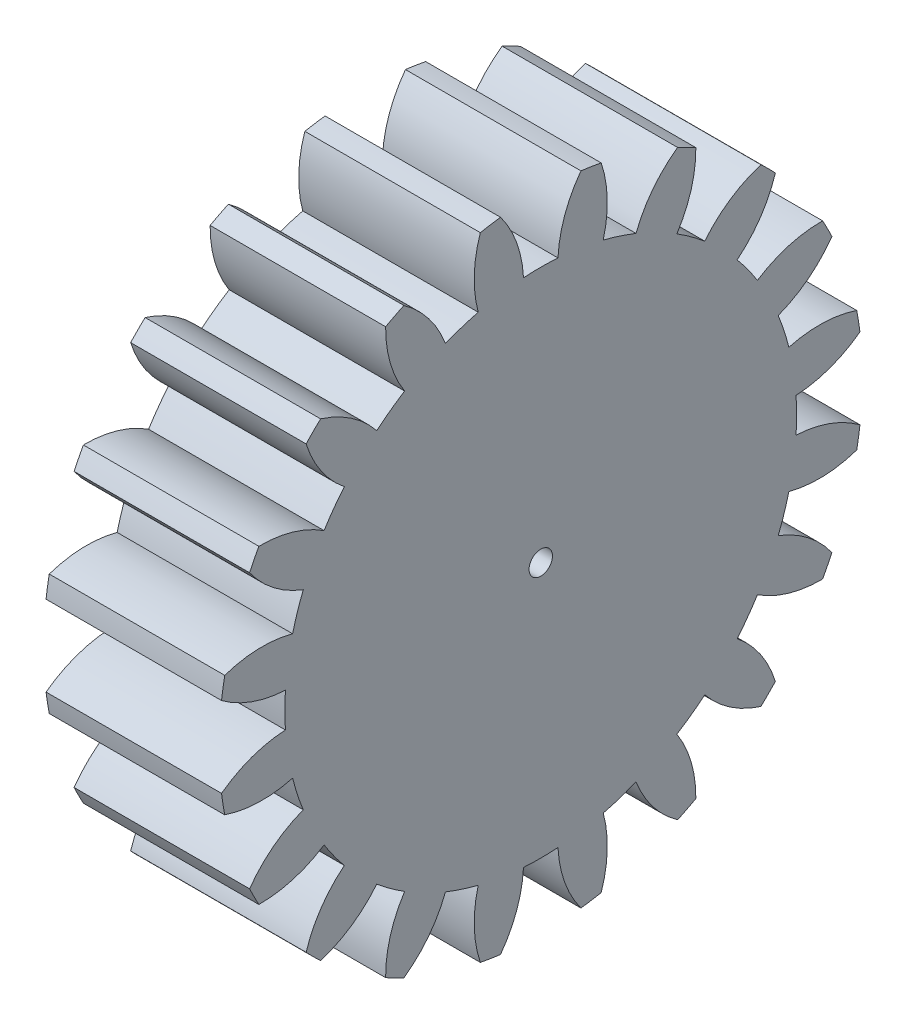
SolidWorks part; units mm, degrees
ref_plane "Plane1" through (0, 0, 0) normal (0, 0, 1) x (1, 0, 0)
ref_plane "Plane2" through (0, 0, 0) normal (0, 1, 0) x (1, 0, 0)
ref_plane "Plane3" through (0, 0, 0) normal (1, 0, 0) x (0, 0, -1)
other "Configuration Table"
sketch "HoldingSke" plane through (0, 0, 0) normal (0, 1, 0) x (1, 0, 0)
  line L0 (0, 0) -> (0.9397, -0.342)
  line L1 (-15, 0) -> (100, 0) construction
  line L2 (0, 0) -> (-2.1039, 2.3779)
  line L3 (0, 0) -> (-11.863, 4.5341)
  line L4 (0, 0) -> (8.1152, 2.9537)
  line L5 (0, 0) -> (-46.8476, -17.4728)
  line L6 (0, 0) -> (-4.9738, -3.3558)
  line L7 (-2.1039, 2.3779) -> (8.6586, 51.2059)
  line L8 (-76.2, 54.61) -> (-76.1, 54.61)
  line L9 (-67.7845, 28.3722) -> (-49.3413, 33.142)
  line L10 (-76.2, 71.12) -> (104.1128, 71.12)
  line L11 (0, 0) -> (-6, 0)
  line L12 (-76.2, 101.6) -> (-76.162, 101.6)
  line L13 (24.9733, 27.94) -> (52.9518, 28.4284)
  line L14 (24.9733, 27.94) -> (24.9743, 27.94)
  line L15 (24.9733, 27.94) -> (100.4006, 29.5858)
  line L16 (-63.627, -1) -> (-12.827, -1)
  circle A0 centre (0, 0) radius 0.4
  circle A1 centre (0, 0) radius 8.749
  circle A2 centre (0, 0) radius 37.5
  circle A3 centre (0, 0) radius 0.4
  dimension "MHD" = 17.498
  dimension "Hub_dia" = 75
  dimension "Bore" = 0.8
  dimension "MBD" = 0.8
  dimension "Num_teeth" = 20
  dimension "Pitch" = 1
  dimension "Overall_len" = 50
  dimension "Show_teeth" = 20
  dimension "Thickness" = 6
  dimension "OAL" = 50.0001
  dimension "T_dim" = 0.1
  dimension "Ap" = 14.5
  dimension "H" = 19.05
  dimension "Pitch_radius" = 180.3128
  dimension "Width" = 6
  dimension "Backlash" = 0.038
  dimension "Addendum_fac" = 1
  dimension "Dedendum_fac" = 1.25
  dimension "Clearance_fac" = 0.25
  dimension "Dedendum_add" = 0.001
  dimension "Module" = 1
sketch "BasProSke" plane through (0, 0, 0) normal (0, 1, 0) x (1, 0, 0)
  line L0 (-10, 0) -> (60, 0) construction
  line L1 (0, 0) -> (0, 11)
  line L2 (0, 0) -> (6, 0)
  line L3 (6, 0) -> (6, 11)
  line L4 (6, 11) -> (0, 11)
  dimension "Thickness" = 6
  dimension "Diameter" = 22
revolve "Base-Revolve" add sketch "BasProSke" angle 360 about L0
sketch "TooCutSke" plane through (0, 0, 0) normal (1, 0, 0) x (0, 0, -1)
  line L1 (0, 0) -> (0, 107) construction
  line L2 (0, 0) -> (-0.8511, 9.9637) construction
  line L3 (0, 0) -> (-3.1206, 19.7028) construction
  line L4 (-0.8511, 9.9637) -> (-1.5603, 9.8514) construction
  arc A0 (0.5894, 8.7291) -> (-0.5894, 8.7291) centre (0, 0) ccw
  arc A1 (1.3917, 10.9372) -> (-1.3917, 10.9372) centre (0, 0) ccw
  circle A2 centre (0, 0) radius 10 construction
  circle A3 centre (0, 0) radius 9.6815 construction
  arc A4 (-0.5894, 8.7291) -> (-1.3917, 10.9372) centre (-4.5843, 8.5273) ccw
  arc A5 (1.3917, 10.9372) -> (0.5894, 8.7291) centre (4.5843, 8.5273) ccw
  dimension "Root_dia" = 17.498
  dimension "Overcut_dia" = 22.0508
  dimension "Pitch_dia" = 20
  dimension "Base_dia" = 19.363
  dimension "Flank_rad" = 4
  dimension "Half_ang" = 9
  dimension "Half_CT" = 0.7181
extrude "ToothCut" cut sketch "TooCutSke" along normal through all
fillet "Breaks" [suppressed] radius 0.02
fillet "RootFillets" [suppressed] radius 0.251
pattern_circular "TeethCuts" count 20 every 18 about axis through (-10, 0, 0) along (1, 0, 0) of "ToothCut", "RootFillets", "Breaks"
sketch "HubNeaOneSke" plane through (0, 0, 0) normal (-1, 0, 0) x (0, 0, 1)
  circle A0 centre (0, 0) radius 8.749
  dimension "Diameter" = 17.498
extrude "HubNearOne" [suppressed] add sketch "HubNeaOneSke" along normal blind 44.0001
sketch "HubNeaBotSke" plane through (0, 0, 0) normal (-1, 0, 0) x (0, 0, 1)
  circle A0 centre (0, 0) radius 8.749
  dimension "Diameter" = 17.498
extrude "HubNearBoth" [suppressed] add sketch "HubNeaBotSke" along normal blind 22
ref_plane "FarPln" through (6, 0, 0) normal (1, 0, 0) x (0, 0, -1)
sketch "HubFarSke" plane through (6, 0, 0) normal (1, 0, 0) x (0, 0, -1)
  circle A0 centre (0, 0) radius 8.749
  dimension "Diameter" = 17.498
extrude "HubFar" [suppressed] add sketch "HubFarSke" along normal blind 22
sketch "BorSke" plane through (0, 0, 0) normal (1, 0, 0) x (0, 0, -1)
  circle A0 centre (0, 0) radius 0.4
  dimension "Diameter" = 0.8
extrude "Bore" cut sketch "BorSke" along normal mid plane 100.0001
sketch "KeySke" plane through (0, 0, 0) normal (1, 0, 0) x (0, 0, -1)
  line L0 (-0.05, 0) -> (-0.05, 0.5)
  line L1 (-0.05, 0.5) -> (0.05, 0.5)
  line L2 (0.05, 0.5) -> (0.05, 0)
  line L3 (0, 0) -> (0, 34) construction
  line L4 (-0.05, 0) -> (0.05, 0)
  dimension "Offset" = 0.5
  dimension "Width" = 0.1
extrude "Keyway" [suppressed] cut sketch "KeySke" along normal mid plane 100.0001
pattern_circular "Keyway2" [suppressed] count 2 every 90 about axis through (-10, 0, 0) along (1, 0, 0)
equation "' \"Module@HoldingSke\" = 6.35"
equation "' \"Num_teeth@HoldingSke\" = 12"
equation "' \"Ap@HoldingSke\" =  20"
equation "' \"Ap@HoldingSke\" = 20"
equation "' \"Width@HoldingSke\" = 0.5 * 25.4"
equation "' \"Hub_dia@HoldingSke\"= 1 * 25.4"
equation "' \"Hub_dia@HoldingSke\" = 1 * 25.4"
equation "' \"Overall_len@HoldingSke\" = 1.0 * 25.4"
equation "' \"Bore@HoldingSke\" = 0.75 * 25.4"
equation "' \"T_dim@HoldingSke\" = 0.1 * 25.4"
equation "' \"Width@KeySke\" = 0.25 * 25.4"
equation "' \"Show_teeth@HoldingSke\" = 13"
equation "' \"Backlash@HoldingSke\" = 0.009 * 25.4"
equation "' \"Addendum_fac@HoldingSke\" = 1.0"
equation "' \"Dedendum_fac@HoldingSke\" = 1.25"
equation "' \"Dedendum_add@HoldingSke\" = 0.00005 * 25.4"
equation "' \"Clearance_fac@HoldingSke\" = 0.25"
equation "\"Pitch@HoldingSke\" = 1 / \"Module@HoldingSke\""
equation "\"Overcut_dia@TooCutSke\" = (\"Num_teeth@HoldingSke\" + 2 * \"Addendum_fac@HoldingSke\") / \"Pitch@HoldingSke\" + 0.002 * 25.4"
equation "\"Pitch_dia@TooCutSke\" = \"Num_teeth@HoldingSke\" / \"Pitch@HoldingSke\""
equation "\"Base_dia@TooCutSke\" = \"Num_teeth@HoldingSke\" / \"Pitch@HoldingSke\" * cos((\"Ap@HoldingSke\"  * 3.14159265 / 180))"
equation "\"Root_dia@TooCutSke\" = (\"Num_teeth@HoldingSke\" + 2) / \"Pitch@HoldingSke\" - 2 * (\"Addendum_fac@HoldingSke\" + \"Dedendum_fac@HoldingSke\") / \"Pitch@HoldingSke\" - \"Dedendum_add@HoldingSke\" * 2"
equation "\"Half_ang@TooCutSke\" = 180 / \"Num_teeth@HoldingSke\""
equation "\"Half_CT@TooCutSke\" = \"Num_teeth@HoldingSke\" / \"Pitch@HoldingSke\" * sin((3.14159265 / 2 / \"Num_teeth@HoldingSke\")) / 2 - 7 * \"Backlash@HoldingSke\" / 4"
equation "\"Flank_rad@TooCutSke\" = \"Num_teeth@HoldingSke\" / \"Pitch@HoldingSke\" / 5"
equation "\"Radius@RootFillets\" = \"Clearance_fac@HoldingSke\" / \"Pitch@HoldingSke\" + \"Dedendum_add@HoldingSke\""
equation "\"Break_rad@Breaks\" = 0.02 / \"Pitch@HoldingSke\""
equation "\"Thickness@HoldingSke\" = \"Width@HoldingSke\""
equation "\"OAL@HoldingSke\" = \"Thickness@HoldingSke\""
equation "\"MHD@HoldingSke\" = (\"Num_teeth@HoldingSke\" + 2) / \"Pitch@HoldingSke\" - 2 * (\"Addendum_fac@HoldingSke\" + \"Dedendum_fac@HoldingSke\")  / \"Pitch@HoldingSke\" - \"Dedendum_add@HoldingSke\" * 2"
equation "\"MBD@HoldingSke\" = (\"Num_teeth@HoldingSke\" + 2) / \"Pitch@HoldingSke\" - 2 * (\"Addendum_fac@HoldingSke\" + \"Dedendum_fac@HoldingSke\")  / \"Pitch@HoldingSke\" - \"Dedendum_add@HoldingSke\" * 2 - 0.002 * 25.4"
equation "\"MHD@HoldingSke\" = ((sgn( \"MHD@HoldingSke\" - \"Hub_dia@HoldingSke\" )-1)*( \"MHD@HoldingSke\" - \"Hub_dia@HoldingSke\" ))/-2+ \"Hub_dia@HoldingSke\""
equation "\"MBD@HoldingSke\" = ((sgn( \"MBD@HoldingSke\" - \"Bore@HoldingSke\" )-1)*( \"MBD@HoldingSke\" - \"Bore@HoldingSke\" ))/-2+ \"Bore@HoldingSke\""
equation "\"OAL@HoldingSke\" = ((sgn( \"OAL@HoldingSke\" - \"Overall_len@HoldingSke\" )+1)*( \"OAL@HoldingSke\" - \"Overall_len@HoldingSke\" ))/2 + \"Overall_len@HoldingSke\" + 0.000002 * 25.4"
equation "\"Num_teeth@TeethCuts\" = int( \"Show_teeth@HoldingSke\" ) + 1"
equation "\"Num_teeth@TeethCuts\" = ((sgn( \"Num_teeth@TeethCuts\" - \"Num_teeth@HoldingSke\" )-1)*( \"Num_teeth@TeethCuts\" - \"Num_teeth@HoldingSke\" ))/-2+ \"Num_teeth@HoldingSke\""
equation "\"Num_teeth@TeethCuts\" = ((sgn( \"Num_teeth@TeethCuts\" - 2.0)+1)*( \"Num_teeth@TeethCuts\" - 2.0))/2 +2.0"
equation "\"Angle@TeethCuts\" = 360.0 / \"Num_teeth@HoldingSke\""
equation "\"Diameter@BasProSke\" = (\"Num_teeth@HoldingSke\" + 2 * \"Addendum_fac@HoldingSke\") / \"Pitch@HoldingSke\""
equation "\"Thickness@BasProSke\"  = \"Thickness@HoldingSke\""
equation "' \"Fillet_rad@BasProSke\" =  \"Thickness@HoldingSke\" * 0.05"
equation "' \"Fillet_rad@BasProSke\" = \"Thickness@HoldingSke\" * 0.05"
equation "\"MHD@HoldingSke\" = ((sgn( \"MHD@HoldingSke\" - \"Root_dia@TooCutSke\" )-1)*( \"MHD@HoldingSke\" - \"Root_dia@TooCutSke\" ))/-2+ \"Root_dia@TooCutSke\""
equation "\"Diameter@HubNeaOneSke\" = \"MHD@HoldingSke\""
equation "\"Length@HubNearOne\" = \"OAL@HoldingSke\" - \"Thickness@BasProSke\""
equation "\"Diameter@HubNeaBotSke\" = \"MHD@HoldingSke\""
equation "\"Length@HubNearBoth\" = ( \"OAL@HoldingSke\" - \"Thickness@BasProSke\" ) / 2.0"
equation "\"Thickness@FarPln\" = \"Thickness@BasProSke\""
equation "\"Diameter@HubFarSke\" = \"MHD@HoldingSke\""
equation "\"Length@HubFar\" = ( \"OAL@HoldingSke\" - \"Thickness@BasProSke\" ) / 2.0"
equation "\"Diameter@BorSke\" = \"MBD@HoldingSke\""
equation "\"D1@Bore\" = \"OAL@HoldingSke\" * 2.0"
equation "\"D1@Keyway\" = \"OAL@HoldingSke\" * 2.0"
equation "\"Offset@KeySke\" = \"T_dim@HoldingSke\" + \"MBD@HoldingSke\" / 2.0"
